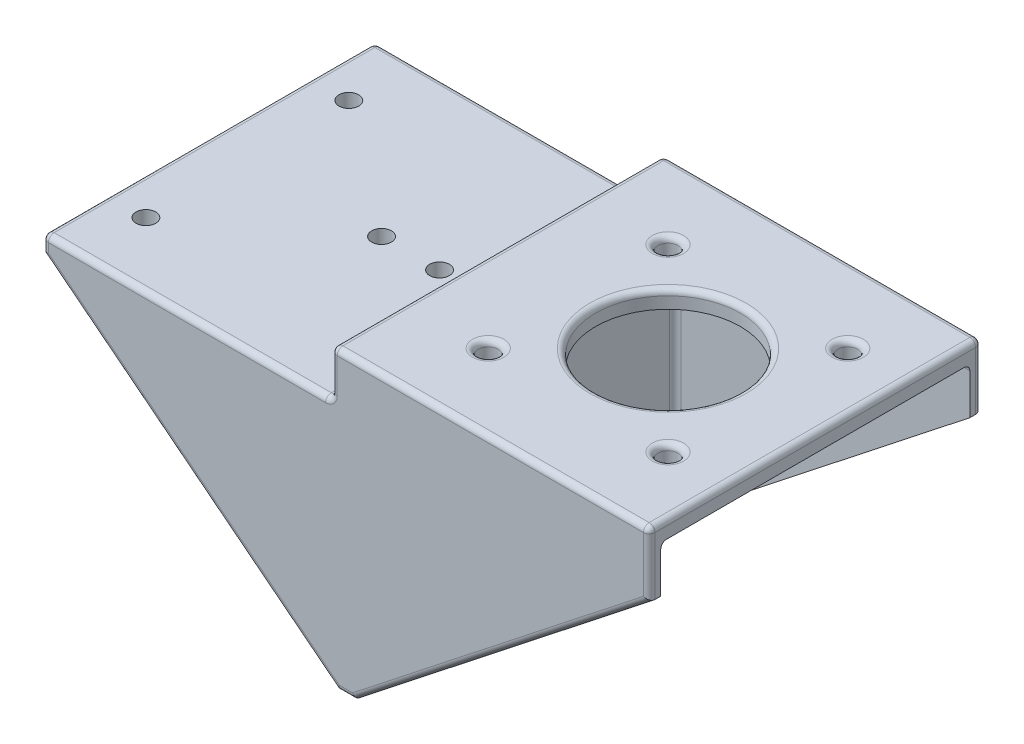
SolidWorks part; units mm, degrees
ref_plane "Front Plane" through (0, 0, 0) normal (0, 0, 1) x (1, 0, 0)
ref_plane "Top Plane" through (0, 0, 0) normal (0, 1, 0) x (1, 0, 0)
ref_plane "Right Plane" through (0, 0, 0) normal (1, 0, 0) x (0, 0, -1)
sketch "Sketch1" plane through (0, 0, 0) normal (0, 1, 0) x (1, 0, 0)
  line L1 (-52.3, 28.65) -> (52.3, 28.65)
  line L2 (-52.3, 28.65) -> (-52.3, -28.65)
  line L3 (-52.3, -28.65) -> (52.3, -28.65)
  line L4 (52.3, 28.65) -> (52.3, -28.65)
  line L5 (-52.3, 28.65) -> (52.3, -28.65) construction
  line L6 (-52.3, -28.65) -> (52.3, 28.65) construction
  point P0 (0, 0)
  dimension "D1" = 57.3
  dimension "D2" = 104.6
extrude "Boss-Extrude1" add sketch "Sketch1" along normal blind 3
sketch "Sketch3" plane through (0, 0, 0) normal (0, -1, 0) x (1, 0, 0)
  line L0 (-52.3, 28.65) -> (52.3, 28.65) construction
  line L1 (-1.5, 28.65) -> (1.5, 28.65)
  line L2 (-1.5, 28.65) -> (-1.5, -28.65)
  line L3 (-1.5, -28.65) -> (1.5, -28.65)
  line L4 (1.5, 28.65) -> (1.5, -28.65)
  line L5 (-1.5, 28.65) -> (1.5, -28.65) construction
  line L6 (-1.5, -28.65) -> (1.5, 28.65) construction
  line L7 (52.3, -28.65) -> (-52.3, -28.65) construction
  point P4 (0, 0)
  dimension "D1" = 3
extrude "Boss-Extrude3" add sketch "Sketch3" along normal blind 40
hole_wizard "M3 Clearance Hole1" positions "Sketch5" profile "Sketch6" hole size "M3" standard "ANSI Metric" end condition through all
sketch "Sketch5" plane through (0, 0, 0) normal (0, -1, 0) x (-1, 0, 0)
  line L1 (-42.4, 15.5) -> (-11.4, 15.5)
  line L2 (-42.4, 15.5) -> (-42.4, -15.5)
  line L3 (-42.4, -15.5) -> (-11.4, -15.5)
  line L4 (-11.4, 15.5) -> (-11.4, -15.5)
  line L5 (-42.4, 15.5) -> (-11.4, -15.5) construction
  line L6 (-42.4, -15.5) -> (-11.4, 15.5) construction
  line L7 (-52.3, -28.65) -> (-1.5, -28.65) construction
  point P2 (-11.4, -15.5)
  point P13 (-42.4, 15.5)
  point P14 (-42.4, -15.5)
  point P15 (-11.4, 15.5)
  point P27 (-26.9, 0)
  point P44 (-26.9, -28.65)
  dimension "D1" = 31
sketch "Sketch6" plane through (11.4, 0, 15.5) normal (1, 0, 0) x (0, 0, -1)
  line L0 (0, 0) -> (0, 3)
  line L1 (0, 3) -> (1.7, 3)
  line L2 (1.7, 3) -> (1.7, 0)
  line L5 (1.7, 0) -> (0, 0)
  line L11 (0, -6.35) -> (0, 107.95) construction
  dimension "Thru Hole Dia." = 3.4
  dimension "Thru Hole Depth" = 3
sketch "Sketch10" plane through (0, 0, 28.65) normal (0, 0, 1) x (1, 0, 0)
  line L0 (-52.3, 0) -> (-1.5, -40)
  line L1 (1.5, -40) -> (52.3, 0)
  line L2 (-52.3, 0) -> (-1.5, 0)
  line L3 (-1.5, 0) -> (-1.5, -40)
  line L4 (1.5, 0) -> (52.3, 0)
  line L5 (1.5, -40) -> (1.5, 0)
extrude "Boss-Extrude4" add sketch "Sketch10" against normal blind 2
ref_plane "Plane1" through (0, 0, 0) normal (0, 0, -1) x (-1, 0, 0)
mirror "Mirror1" about plane through (0, 0, 0) normal (0, 0, -1) of "Boss-Extrude4"
sketch "Sketch11" plane through (0, 0, 0) normal (0, -1, 0) x (1, 0, 0)
  line L1 (11.4, -15.5) -> (42.4, 15.5) construction
  circle A0 centre (26.9, 0) radius 12.5
  dimension "D1" = 25
extrude "Cut-Extrude1" cut sketch "Sketch11" against normal through all
hole_wizard "M3 Clearance Hole3" positions "Sketch12" profile "Sketch13" hole size "M3" standard "ANSI Metric" end condition through all
sketch "Sketch12" plane through (0, 0, 0) normal (0, -1, 0) x (-1, 0, 0)
  line L1 (8.1618, 17.5) -> (45.6382, 17.5)
  line L2 (8.1618, 17.5) -> (8.1618, -17.5)
  line L3 (8.1618, -17.5) -> (45.6382, -17.5)
  line L4 (45.6382, 17.5) -> (45.6382, -17.5)
  line L5 (8.1618, 17.5) -> (45.6382, -17.5) construction
  line L6 (8.1618, -17.5) -> (45.6382, 17.5) construction
  line L8 (1.5, -26.65) -> (52.3, -26.65) construction
  point P2 (45.6382, -17.5)
  point P19 (8.1618, 17.5)
  point P20 (8.1618, -17.5)
  point P21 (45.6382, 17.5)
  point P25 (26.9, 0)
  point P53 (26.9, -26.65)
  dimension "D1" = 35
sketch "Sketch13" plane through (-45.6382, 0, 17.5) normal (1, 0, 0) x (0, 0, -1)
  line L0 (0, 0) -> (0, 3)
  line L1 (0, 3) -> (1.7, 3)
  line L2 (1.7, 3) -> (1.7, 0)
  line L5 (1.7, 0) -> (0, 0)
  line L11 (0, -6.35) -> (0, 107.95) construction
  dimension "Thru Hole Dia." = 3.4
  dimension "Thru Hole Depth" = 3
sketch "Sketch14" plane through (0, 3, 0) normal (0, 1, 0) x (1, 0, 0)
  circle A0 centre (-22.5, 0) radius 1.7 construction
  circle A1 centre (-12.5, 0) radius 1.7 construction
  circle A2 centre (-22.5, 0) radius 1.7
  circle A3 centre (-12.5, 0) radius 1.7
extrude "Cut-Extrude2" cut sketch "Sketch14" against normal through all
sketch "Sketch16" plane through (0, 3, 0) normal (0, 1, 0) x (1, 0, 0)
  line L0 (-52.3, -28.65) -> (52.3, -28.65) construction
  line L1 (52.3, 28.65) -> (1.5, 28.65)
  line L2 (52.3, 28.65) -> (52.3, -28.65)
  line L3 (52.3, -28.65) -> (1.5, -28.65)
  line L4 (1.5, 28.65) -> (1.5, -28.65)
  line L5 (52.3, 28.65) -> (1.5, -28.65) construction
  line L6 (52.3, -28.65) -> (1.5, 28.65) construction
  line L7 (1.5, 26.65) -> (1.5, -26.65) construction
  circle A0 centre (26.9, 0) radius 12.5 construction
  circle A1 centre (42.4, 15.5) radius 1.7 construction
  circle A2 centre (42.4, -15.5) radius 1.7 construction
  circle A3 centre (11.4, -15.5) radius 1.7 construction
  circle A4 centre (11.4, 15.5) radius 1.7 construction
  circle A5 centre (26.9, 0) radius 12.5
  circle A6 centre (42.4, 15.5) radius 1.7
  circle A7 centre (42.4, -15.5) radius 1.7
  circle A8 centre (11.4, -15.5) radius 1.7
  circle A9 centre (11.4, 15.5) radius 1.7
  point P4 (26.9, 0)
extrude "Boss-Extrude5" add sketch "Sketch16" along normal blind 8
sketch "Sketch17" plane through (0, 0, 0) normal (0, -1, 0) x (1, 0, 0)
  line L1 (1.5, 26.65) -> (52.3, 26.65)
  line L2 (1.5, 26.65) -> (1.5, -26.65)
  line L3 (1.5, -26.65) -> (52.3, -26.65)
  line L4 (52.3, 26.65) -> (52.3, -26.65)
  line L5 (1.5, 26.65) -> (52.3, -26.65) construction
  line L6 (1.5, -26.65) -> (52.3, 26.65) construction
  point P4 (26.9, 0)
extrude "Cut-Extrude3" cut sketch "Sketch17" against normal blind 8
sketch "Sketch18" plane through (1.5, 0, 0) normal (-1, 0, 0) x (0, 0, 1)
  line L1 (-28.65, 11) -> (28.65, 11)
  line L2 (-28.65, 11) -> (-28.65, 3)
  line L3 (-28.65, 3) -> (28.65, 3)
  line L4 (28.65, 11) -> (28.65, 3)
  line L5 (-28.65, 11) -> (28.65, 3) construction
  line L6 (-28.65, 3) -> (28.65, 11) construction
  point P4 (0, 7)
extrude "Boss-Extrude6" add sketch "Sketch18" along normal blind 4
fillet "Fillet1" radius 1 34 edges at (-52.3, 1.5, -28.65) (-26.9, -20, -28.65) (0, -40, -28.65) (26.9, -20, -28.65) (52.3, 5.5, -28.65) (-52.3, 3, 0) (-27.4, 3, -28.65) (0, -40, 28.65) (-26.9, -20, 28.65) (-52.3, 1.5, 28.65) (-27.4, 3, 28.65) (52.3, 5.5, 28.65) (26.9, -20, 28.65) (11.4, 11, -13.8) (11.4, 11, 17.2) (42.4, 11, 17.2) (42.4, 11, -13.8) (26.9, 11, 12.5) (24.9, 11, 28.65) (24.9, 11, -28.65) (52.3, 11, 0) (-2.5, 11, 0) (-2.5, 7, 28.65) (-2.5, 3, 0) (-2.5, 7, -28.65) (1.5, -16, -26.65) (26.9, 8, -26.65) (26.9, 8, 26.65) (1.5, -16, 26.65) (-1.5, -20, 26.65) (-26.9, 0, 26.65) (-26.9, 0, -26.65) (-1.5, -20, -26.65) (-1.5, 0, 0)
